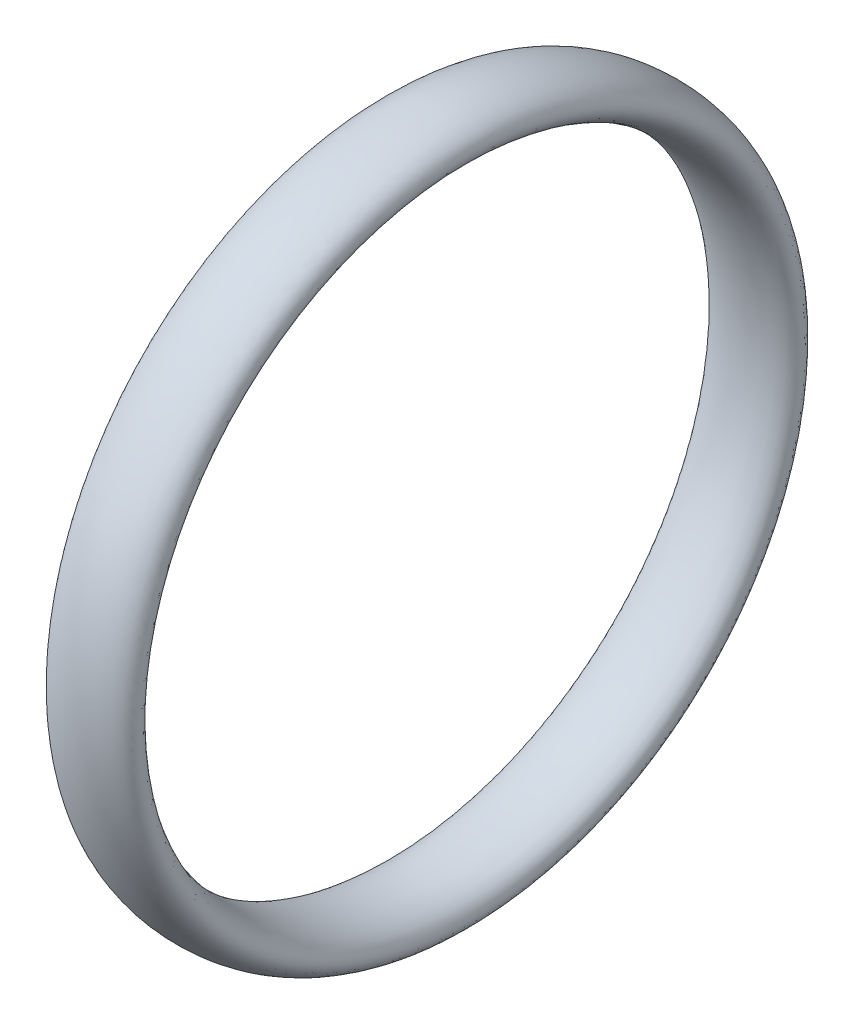
SolidWorks part; units mm, degrees
ref_plane "Front Plane" through (0, 0, 0) normal (0, 0, 1) x (1, 0, 0)
ref_plane "Top Plane" through (0, 0, 0) normal (0, 1, 0) x (1, 0, 0)
ref_plane "Right Plane" through (0, 0, 0) normal (1, 0, 0) x (0, 0, -1)
sketch "Sketch1" plane through (0, 0, 0) normal (0, 0, 1) x (1, 0, 0)
  line L0 (0, 0) -> (12.1059, 0) construction
  line L1 (0, 0) -> (0, 8.6471) construction
  ellipse E0 centre (0, 7.5) end of major axis (1, 7.5) minor radius 0.5
  dimension "D1" = 15
  dimension "D2" = 1
  dimension "D3" = 2
revolve "Revolve1" add sketch "Sketch1" angle 360 about L0
